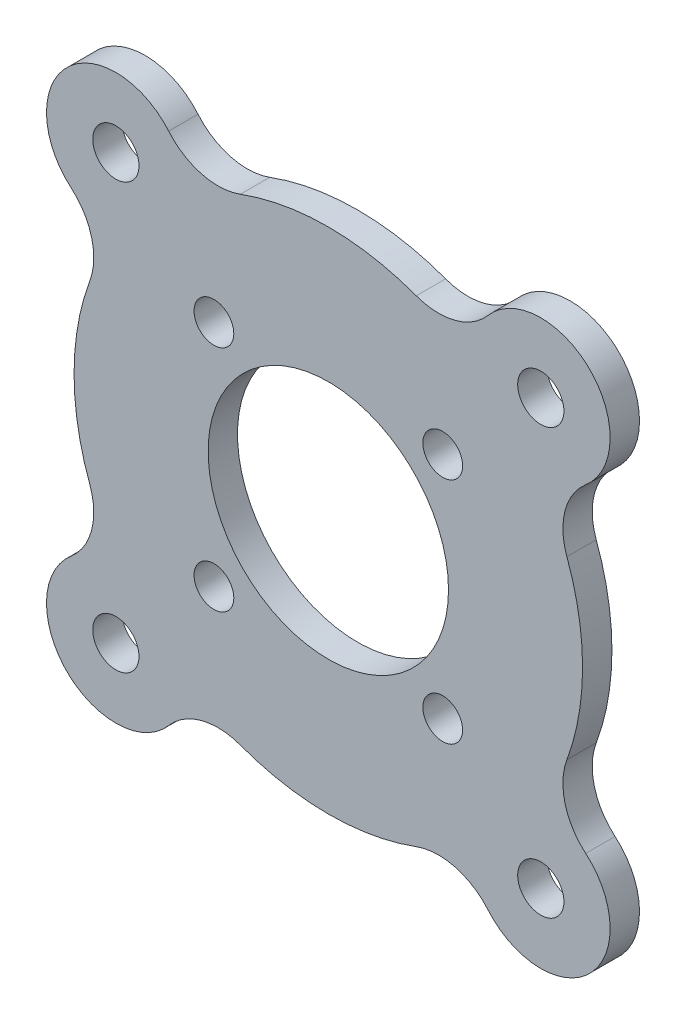
SolidWorks part; units mm, degrees
material "6061 Alloy"
ref_plane "Front Plane" through (0, 0, 0) normal (0, 0, 1) x (1, 0, 0)
ref_plane "Top Plane" through (0, 0, 0) normal (0, 1, 0) x (1, 0, 0)
ref_plane "Right Plane" through (0, 0, 0) normal (1, 0, 0) x (0, 0, -1)
sketch "Sketch1" plane through (0, 0, 0) normal (0, 0, 1) x (1, 0, 0)
  line L1 (-22.981, -22.981) -> (22.981, -22.981) construction
  line L2 (-22.981, -22.981) -> (-22.981, 22.981) construction
  line L3 (-22.981, 22.981) -> (22.981, 22.981) construction
  line L4 (22.981, -22.981) -> (22.981, 22.981) construction
  line L5 (-22.981, -22.981) -> (22.981, 22.981) construction
  line L6 (-22.981, 22.981) -> (22.981, -22.981) construction
  circle A0 centre (0, 0) radius 27.5
  circle A1 centre (0, 0) radius 32.5 construction
  circle A2 centre (-22.981, 22.981) radius 7.5
  circle A3 centre (-22.981, -22.981) radius 7.5
  circle A4 centre (22.981, -22.981) radius 7.5
  circle A5 centre (22.981, 22.981) radius 7.5
  dimension "D1" = 55
  dimension "D2" = 65
  dimension "D3" = 15
extrude ".125 in sheet" add sketch "Sketch1" along normal mid plane 3.175 contours A5 A0 A2 A3 A4 | A0 A2 | A0 A5 | A0 A4 | A0 A3 | A0 A3 | A0 A2 | A0 A5 | A0 A4
fillet "Fillet1" radius 7 8 edges at (15.4853, 22.7256, 0) (22.7256, 15.4853, 0) (22.7256, -15.4853, 0) (15.4853, -22.7256, 0) (-15.4853, -22.7256, 0) (-22.7256, -15.4853, 0) (-22.7256, 15.4853, 0) (-15.4853, 22.7256, 0)
sketch "Sketch2" plane through (0, 0, 1.5875) normal (0, 0, 1) x (1, 0, 0)
  circle A0 centre (0, 0) radius 13
  dimension "D1" = 26
extrude "Cut-Extrude1" cut sketch "Sketch2" against normal through all
hole_wizard "M4 Clearance Hole1" positions "Sketch4" profile "Sketch3" hole size "M4" standard "ANSI Metric" end condition through all
sketch "Sketch4" plane through (0, 0, 1.5875) normal (0, 0, 1) x (1, 0, 0)
  line L1 (12.3744, -12.3744) -> (-12.3744, -12.3744)
  line L2 (12.3744, -12.3744) -> (12.3744, 12.3744)
  line L3 (12.3744, 12.3744) -> (-12.3744, 12.3744)
  line L4 (-12.3744, -12.3744) -> (-12.3744, 12.3744)
  line L5 (12.3744, -12.3744) -> (-12.3744, 12.3744) construction
  line L6 (12.3744, 12.3744) -> (-12.3744, -12.3744) construction
  circle A0 centre (0, 0) radius 17.5
  point P0 (-12.3744, 12.3744)
  point P2 (12.3744, 12.3744)
  point P4 (12.3744, -12.3744)
  point P6 (-12.3744, -12.3744)
  dimension "D1" = 35
sketch "Sketch3" plane through (-12.3744, 12.3744, 1.5875) normal (1, 0, 0) x (0, -1, 0)
  line L0 (0, 0) -> (0, 3.175)
  line L1 (0, 3.175) -> (2.15, 3.175)
  line L2 (2.15, 3.175) -> (2.15, 0)
  line L5 (2.15, 0) -> (0, 0)
  line L11 (0, -6.35) -> (0, 107.95) construction
  dimension "Thru Hole Dia." = 4.3
  dimension "Thru Hole Depth" = 3.175
hole_wizard "Ø5.0 Reamed over for shoulder bolt" positions "Sketch6" profile "Sketch5" hole size "Ø5.0" standard "ANSI Metric" end condition through all
sketch "Sketch6" plane through (0, 0, 1.5875) normal (0, 0, 1) x (1, 0, 0)
  point P0 (-22.981, 22.981)
  point P3 (22.981, 22.981)
  point P6 (22.981, -22.981)
  point P9 (-22.981, -22.981)
sketch "Sketch5" plane through (-22.981, 22.981, 1.5875) normal (1, 0, 0) x (0, -1, 0)
  line L0 (0, 0) -> (0, 3.175)
  line L1 (0, 3.175) -> (2.5, 3.175)
  line L2 (2.5, 3.175) -> (2.5, 0)
  line L5 (2.5, 0) -> (0, 0)
  line L11 (0, -6.35) -> (0, 107.95) construction
  dimension "Thru Hole Dia." = 5
  dimension "Thru Hole Depth" = 3.175
